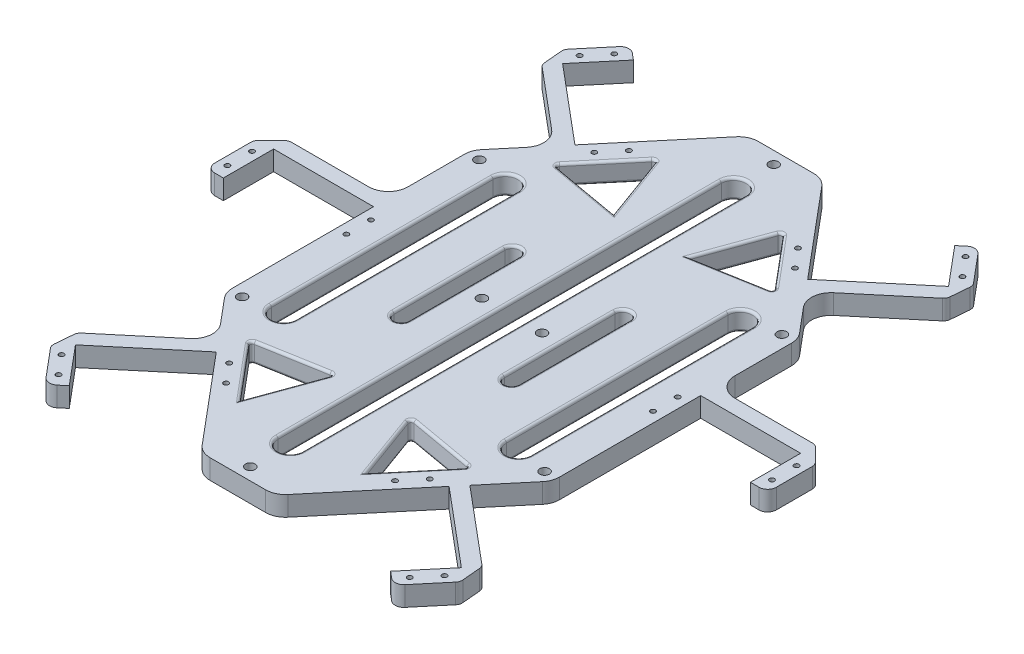
SolidWorks part; units mm, degrees
material "ABS"
ref_plane "Front Plane" through (0, 0, 0) normal (0, 0, 1) x (1, 0, 0)
ref_plane "Top Plane" through (0, 0, 0) normal (0, 1, 0) x (1, 0, 0)
ref_plane "Right Plane" through (0, 0, 0) normal (1, 0, 0) x (0, 0, -1)
sketch "Sketch1" plane through (0, 0, 0) normal (0, 1, 0) x (1, 0, 0)
  line L14 (0, 0) -> (0, 100)
  line L21 (0, 100) -> (51.423, 161.2836)
  line L22 (51.423, 161.2836) -> (81.423, 161.2836)
  line L23 (81.423, 161.2836) -> (132.846, 100)
  line L24 (132.846, 100) -> (132.846, 0)
  line L25 (132.846, 0) -> (81.423, -61.2836)
  line L26 (81.423, -61.2836) -> (51.423, -61.2836)
  line L27 (51.423, -61.2836) -> (0, 0)
  dimension "D4" = 80
  dimension "D1" = 100
  dimension "D2" = 80
  dimension "D3" = 30
  dimension "D5" = 80
  dimension "D6" = 30
  dimension "D7" = 140
  dimension "D8" = 140
  dimension "D9" = 140
  dimension "D10" = 140
extrude "Boss-Extrude1" add sketch "Sketch1" along normal blind 8
sketch "Sketch2" plane through (0, 8, 0) normal (0, 1, 0) x (1, 0, 0)
  line L0 (0, 50) -> (132.846, 50) construction
  line L1 (0, 100) -> (0, 0) construction
  line L2 (132.846, 0) -> (132.846, 100) construction
  line L3 (66.423, 161.2836) -> (66.423, -61.2836) construction
  line L4 (81.423, 161.2836) -> (51.423, 161.2836) construction
  line L5 (51.423, -61.2836) -> (81.423, -61.2836) construction
  line L6 (25.7115, -30.6418) -> (11.6576, -42.4344) construction
  line L7 (39.773, -0.8) -> (93.073, -0.8) construction
  line L8 (39.773, -0.8) -> (39.773, 100.8) construction
  line L9 (39.773, 100.8) -> (93.073, 100.8) construction
  line L10 (93.073, -0.8) -> (93.073, 100.8) construction
  line L11 (39.773, -0.8) -> (93.073, 100.8) construction
  line L12 (39.773, 100.8) -> (93.073, -0.8) construction
  line L13 (0, 0) -> (51.423, -61.2836) construction
  circle A5 centre (25.6767, -24.144) radius 1
  circle A6 centre (32.1045, -31.8044) radius 1
  circle A7 centre (4.15, 55) radius 1
  circle A8 centre (4.15, 45) radius 1
  circle A9 centre (32.1045, 131.8044) radius 1
  circle A10 centre (25.6767, 124.144) radius 1
  circle A11 centre (107.1694, 124.144) radius 1
  circle A12 centre (100.7415, 131.8044) radius 1
  circle A13 centre (128.696, 45) radius 1
  circle A14 centre (128.696, 55) radius 1
  circle A15 centre (100.7415, -31.8044) radius 1
  circle A16 centre (107.1694, -24.144) radius 1
  point P12 (66.423, 50)
  dimension "D15" = 2
  dimension "D16" = 2
  dimension "D21" = 2
  dimension "D22" = 2
  dimension "D1" = 101.6
  dimension "D2" = 53.3
  dimension "D17" = 4.15
  dimension "D18" = 4.15
  dimension "D19" = 10
  dimension "D20" = 5
  dimension "D23" = 4.15
  dimension "D24" = 4.15
  dimension "D25" = 10
  dimension "D26" = 5
extrude "mounting holes" cut sketch "Sketch2" against normal through all
sketch "Sketch3" plane through (0, 8, 0) normal (0, 1, 0) x (1, 0, 0)
  line L0 (66.423, 161.2836) -> (66.423, -61.2836) construction
  line L1 (81.423, 161.2836) -> (51.423, 161.2836) construction
  line L2 (51.423, -61.2836) -> (81.423, -61.2836) construction
  line L3 (0, 50) -> (132.846, 50) construction
  line L4 (0, 100) -> (0, 0) construction
  line L5 (132.846, 0) -> (132.846, 100) construction
  line L6 (66.423, 140) -> (66.423, -40) construction
  line L7 (71.423, 140) -> (71.423, -40)
  line L8 (61.423, 140) -> (61.423, -40)
  line L12 (18.7108, 5) -> (18.7108, 95) construction
  line L13 (13.7108, 5) -> (13.7108, 95)
  line L14 (23.7108, 5) -> (23.7108, 95)
  line L15 (21.5683, -11.7715) -> (40.8519, -34.7528)
  line L16 (40.8519, -34.7528) -> (51.1125, -6.562)
  line L17 (51.1125, -6.562) -> (21.5683, -11.7715)
  line L18 (0, 0) -> (51.423, -61.2836) construction
  line L22 (44.023, 72.5) -> (44.023, 27.5) construction
  line L23 (47.023, 72.5) -> (47.023, 27.5)
  line L24 (41.023, 72.5) -> (41.023, 27.5)
  line L25 (21.5683, 111.7715) -> (40.8519, 134.7528)
  line L26 (40.8519, 134.7528) -> (51.1125, 106.562)
  line L27 (51.1125, 106.562) -> (21.5683, 111.7715)
  line L28 (111.2777, -11.7715) -> (91.9941, -34.7528)
  line L29 (91.9941, -34.7528) -> (81.7335, -6.562)
  line L30 (81.7335, -6.562) -> (111.2777, -11.7715)
  line L31 (88.823, 72.5) -> (88.823, 27.5) construction
  line L32 (85.823, 72.5) -> (85.823, 27.5)
  line L33 (91.823, 72.5) -> (91.823, 27.5)
  line L34 (114.1353, 5) -> (114.1353, 95) construction
  line L35 (119.1353, 5) -> (119.1353, 95)
  line L36 (109.1353, 5) -> (109.1353, 95)
  line L37 (81.7335, 106.562) -> (111.2777, 111.7715)
  line L38 (91.9941, 134.7528) -> (81.7335, 106.562)
  line L39 (111.2777, 111.7715) -> (91.9941, 134.7528)
  arc A0 (71.423, 140) -> (61.423, 140) centre (66.423, 140) ccw
  arc A1 (61.423, -40) -> (71.423, -40) centre (66.423, -40) ccw
  arc A2 (13.7108, 5) -> (23.7108, 5) centre (18.7108, 5) ccw
  arc A3 (23.7108, 95) -> (13.7108, 95) centre (18.7108, 95) ccw
  arc A4 (47.023, 72.5) -> (41.023, 72.5) centre (44.023, 72.5) ccw
  arc A5 (41.023, 27.5) -> (47.023, 27.5) centre (44.023, 27.5) ccw
  arc A6 (85.823, 72.5) -> (91.823, 72.5) centre (88.823, 72.5) cw
  arc A7 (91.823, 27.5) -> (85.823, 27.5) centre (88.823, 27.5) cw
  arc A8 (119.1353, 5) -> (109.1353, 5) centre (114.1353, 5) cw
  arc A9 (109.1353, 95) -> (119.1353, 95) centre (114.1353, 95) cw
  point P14 (66.423, 50)
  point P23 (18.7108, 50)
  point P32 (44.023, 50)
  point P46 (88.823, 50)
  point P53 (114.1353, 50)
  dimension "D2" = 180
  dimension "D3" = 5
  dimension "D8" = 3
  dimension "D1" = 90
  dimension "D4" = 30
  dimension "D5" = 30
  dimension "D6" = 30
  dimension "D7" = 45
  dimension "D9" = 25.4
extrude "Cut-Extrude1" cut sketch "Sketch3" against normal through all
sketch "Sketch4" plane through (0, 8, 0) normal (0, 1, 0) x (1, 0, 0)
  line L0 (25.7115, -30.6418) -> (-23.1285, -71.6234) construction
  line L1 (0, 0) -> (51.423, -61.2836) construction
  line L2 (0, 50) -> (-64.2755, 50) construction
  line L3 (0, 100) -> (0, 0) construction
  line L4 (25.7115, 130.6418) -> (-14.5433, 164.4196) construction
  line L5 (51.423, 161.2836) -> (0, 100) construction
  line L6 (107.1345, 130.6418) -> (143.3112, 160.9976) construction
  line L7 (132.846, 100) -> (81.423, 161.2836) construction
  line L8 (132.846, 50) -> (189.4522, 50) construction
  line L9 (132.846, 0) -> (132.846, 100) construction
  line L10 (107.1345, -30.6418) -> (151.3622, -67.7532) construction
  line L11 (81.423, -61.2836) -> (132.846, 0) construction
  line L12 (-11.3581, -48.6928) -> (19.2836, -22.9813) construction
  line L13 (19.2836, -22.9813) -> (32.1394, -38.3022) construction
  line L14 (32.1394, -38.3022) -> (1.4976, -64.0137) construction
  line L15 (1.4976, -64.0137) -> (-11.3581, -48.6928) construction
  line L24 (-5.3899, -56.739) -> (-18.1892, -41.4853) construction
  line L25 (1.2652, -37.8395) -> (19.1551, -22.8281) construction
  line L26 (19.1551, -22.8281) -> (-11.9463, -48.9253)
  line L27 (-1.778, -67.0233) -> (8.4573, -58.435) construction
  line L28 (-11.9463, -48.9253) -> (1.1665, -64.5526)
  line L29 (1.1665, -64.5526) -> (-4.1958, -69.0521)
  line L30 (-4.1958, -69.0521) -> (-21.1654, -48.8285)
  line L31 (-21.1654, -48.8285) -> (15.2983, -18.2319)
  line L32 (15.2983, -18.2319) -> (19.1551, -22.8281)
  line L33 (0, 60.2) -> (-40.6, 60.2)
  line L34 (-40.6, 60.2) -> (-40.6, 39.8)
  line L35 (-40.6, 39.8) -> (-47.6, 39.8)
  line L36 (-47.6, 39.8) -> (-47.6, 66.2)
  line L37 (-47.6, 66.2) -> (0, 66.2)
  line L38 (0, 66.2) -> (0, 60.2)
  line L39 (1.1665, 164.5526) -> (-4.1958, 169.0521)
  line L40 (-4.1958, 169.0521) -> (-21.1654, 148.8285)
  line L41 (-11.9463, 148.9253) -> (1.1665, 164.5526)
  line L42 (-21.1654, 148.8285) -> (15.2983, 118.2319)
  line L43 (15.2983, 118.2319) -> (19.1551, 122.8281)
  line L44 (19.1551, 122.8281) -> (-11.9463, 148.9253)
  line L45 (66.423, -61.2836) -> (66.423, 161.2836) construction
  line L46 (51.423, -61.2836) -> (81.423, -61.2836) construction
  line L47 (81.423, 161.2836) -> (51.423, 161.2836) construction
  line L48 (134.624, -67.0233) -> (124.3888, -58.435) construction
  line L49 (131.5808, -37.8395) -> (113.6909, -22.8281) construction
  line L50 (138.2359, -56.739) -> (151.0352, -41.4853) construction
  line L51 (131.3484, -64.0137) -> (144.2042, -48.6928) construction
  line L52 (100.7066, -38.3022) -> (131.3484, -64.0137) construction
  line L53 (113.5624, -22.9813) -> (100.7066, -38.3022) construction
  line L54 (144.2042, -48.6928) -> (113.5624, -22.9813) construction
  line L55 (107.1345, 130.6418) -> (147.3894, 164.4196) construction
  line L56 (132.846, 50) -> (197.1216, 50) construction
  line L57 (107.1345, -30.6418) -> (155.9746, -71.6234) construction
  line L58 (113.6909, 122.8281) -> (144.7924, 148.9253)
  line L59 (117.5477, 118.2319) -> (113.6909, 122.8281)
  line L60 (154.0114, 148.8285) -> (117.5477, 118.2319)
  line L61 (144.7924, 148.9253) -> (131.6795, 164.5526)
  line L62 (137.0418, 169.0521) -> (154.0114, 148.8285)
  line L63 (131.6795, 164.5526) -> (137.0418, 169.0521)
  line L64 (132.846, 66.2) -> (132.846, 60.2)
  line L65 (180.446, 66.2) -> (132.846, 66.2)
  line L66 (180.446, 39.8) -> (180.446, 66.2)
  line L67 (173.446, 39.8) -> (180.446, 39.8)
  line L68 (173.446, 60.2) -> (173.446, 39.8)
  line L69 (132.846, 60.2) -> (173.446, 60.2)
  line L70 (117.5477, -18.2319) -> (113.6909, -22.8281)
  line L71 (154.0114, -48.8285) -> (117.5477, -18.2319)
  line L72 (137.0418, -69.0521) -> (154.0114, -48.8285)
  line L73 (131.6795, -64.5526) -> (137.0418, -69.0521)
  line L74 (144.7924, -48.9253) -> (131.6795, -64.5526)
  line L75 (113.6909, -22.8281) -> (144.7924, -48.9253)
  dimension "D1" = 40
  dimension "D2" = 20
  dimension "D3" = 40
  dimension "D4" = 40.6
  dimension "D5" = 0.2
  dimension "D6" = 0.2
  dimension "D7" = 7
  dimension "D8" = 26.4
  dimension "D9" = 10.2
  dimension "D10" = 40.6
  dimension "D11" = 20.4
  dimension "D12" = 7
  dimension "D13" = 26.4
  dimension "D14" = 10.2
extrude "Boss-Extrude2" add sketch "Sketch4" against normal blind 8
sketch "Sketch5" plane through (0, 8, 0) normal (0, 1, 0) x (1, 0, 0)
  line L0 (25.6767, -24.144) -> (32.1045, -31.8044) construction
  line L1 (28.8906, -27.9742) -> (21.384, -34.273) construction
  line L2 (4.15, 55) -> (4.15, 45) construction
  line L3 (4.15, 50) -> (-23.5507, 50) construction
  line L4 (71.423, 50) -> (32.1045, 50) construction
  line L5 (71.423, -40) -> (71.423, 140) construction
  line L6 (66.423, -61.2836) -> (66.423, 0) construction
  line L7 (51.423, -61.2836) -> (81.423, -61.2836) construction
  circle A0 centre (-11.3233, -55.1906) radius 1
  circle A1 centre (-4.8954, -62.8511) radius 1
  circle A2 centre (-44.15, 55) radius 1
  circle A3 centre (-44.15, 45) radius 1
  circle A4 centre (-4.8954, 162.8511) radius 1
  circle A5 centre (-11.3233, 155.1906) radius 1
  circle A6 centre (144.1693, 155.1906) radius 1
  circle A7 centre (137.7414, 162.8511) radius 1
  circle A8 centre (176.996, 45) radius 1
  circle A9 centre (176.996, 55) radius 1
  circle A10 centre (137.7414, -62.8511) radius 1
  circle A11 centre (144.1693, -55.1906) radius 1
  dimension "D1" = 2
  dimension "D2" = 2
  dimension "D7" = 2
  dimension "D8" = 2
  dimension "D3" = 48.3
  dimension "D4" = 48.3
  dimension "D5" = 10
  dimension "D6" = 5
  dimension "D9" = 10
  dimension "D10" = 5
  dimension "D11" = 48.3
  dimension "D12" = 48.3
extrude "Cut-Extrude2" cut sketch "Sketch5" against normal through all
fillet "Fillet1" radius 8 1 edges at (15.2983, 4, -118.2319)
fillet "Fillet2" radius 8 1 edges at (0, 4, -100)
fillet "Fillet3" radius 8 1 edges at (51.423, 4, -161.2836)
fillet "Fillet4" radius 8 1 edges at (0, 4, 0)
fillet "Fillet5" radius 8 1 edges at (132.846, 4, -100)
fillet "Fillet6" radius 8 1 edges at (81.423, 4, 61.2836)
fillet "Fillet7" radius 8 1 edges at (81.423, 4, -161.2836)
fillet "Fillet8" radius 8 1 edges at (51.423, 4, 61.2836)
fillet "Fillet9" radius 8 1 edges at (132.846, 4, 0)
fillet "Fillet10" radius 8 1 edges at (132.846, 4, -66.2)
fillet "Fillet11" radius 8 1 edges at (117.5477, 4, -118.2319)
fillet "Fillet12" radius 8 1 edges at (15.2983, 4, 18.2319)
fillet "Fillet13" radius 8 1 edges at (0, 4, -66.2)
fillet "Fillet16" radius 1 72 edges at (96.5056, 0, -109.1667) (96.5056, 8, -109.1667) (86.8638, 0, -120.6574) (86.8638, 8, -120.6574) (45.9822, 0, -120.6574) (45.9822, 8, -120.6574) (36.3404, 0, -109.1667) (36.3404, 8, -109.1667) (45.9822, 0, 20.6574) (45.9822, 8, 20.6574) (31.2101, 0, 23.2621) (31.2101, 8, 23.2621) (101.6359, 0, 23.2621) (101.6359, 8, 23.2621) (86.8638, 0, 20.6574) (86.8638, 8, 20.6574) (114.1353, 0, -100) (119.1353, 0, -50) (114.1353, 0, 0) (114.1353, 8, -100) (119.1353, 8, -50) (114.1353, 8, 0) (18.7108, 0, -100) (23.7108, 0, -50) (18.7108, 0, 0) (18.7108, 8, -100) (23.7108, 8, -50) (18.7108, 8, 0) (88.823, 0, -75.5) (91.823, 0, -50) (88.823, 0, -24.5) (88.823, 8, -75.5) (91.823, 8, -50) (88.823, 8, -24.5) (44.023, 0, -75.5) (47.023, 0, -50) (44.023, 0, -24.5) (44.023, 8, -75.5) (47.023, 8, -50) (44.023, 8, -24.5) (66.423, 8, -145) (71.423, 8, -50) (66.423, 8, 45) (111.2777, 4, -111.7715) (101.6359, 0, -123.2621) (91.9941, 4, -134.7528) (101.6359, 8, -123.2621) (40.8519, 4, -134.7528) (31.2101, 0, -123.2621) (21.5683, 4, -111.7715) (31.2101, 8, -123.2621) (51.1125, 4, 6.562) (36.3404, 0, 9.1667) (21.5683, 4, 11.7715) (36.3404, 8, 9.1667) (111.2777, 4, 11.7715) (96.5056, 0, 9.1667) (81.7335, 4, 6.562) (96.5056, 8, 9.1667) (109.1353, 0, -50) (109.1353, 8, -50) (13.7108, 0, -50) (13.7108, 8, -50) (85.823, 0, -50) (85.823, 8, -50) (41.023, 0, -50) (41.023, 8, -50) (61.423, 8, -50) (66.423, 0, 45) (61.423, 0, -50) (66.423, 0, -145) (71.423, 0, -50)
fillet "Fillet18" radius 3.5 6 edges at (-47.6, 4, -39.8) (137.0418, 4, 69.0521) (180.446, 4, -39.8) (137.0418, 4, -169.0521) (-4.1958, 4, -169.0521) (-4.1958, 4, 69.0521)
chamfer "Chamfer2" distance 7 angle 45 6 edges at (-21.1654, 4, 48.8285) (154.0114, 4, 48.8285) (180.446, 4, -66.2) (154.0114, 4, -148.8285) (-21.1654, 4, -148.8285) (-47.6, 4, -66.2)
fillet "Fillet21" radius 3 12 edges at (-15.8031, 4, 44.329) (-16.6659, 4, 54.1909) (-16.6659, 4, -154.1909) (-15.8031, 4, -144.329) (-47.6, 4, -59.2) (-40.6, 4, -66.2) (148.6491, 4, -144.329) (149.5119, 4, -154.1909) (180.446, 4, -59.2) (173.446, 4, -66.2) (148.6491, 4, 44.329) (149.5119, 4, 54.1909)
sketch "Sketch6" plane through (0, 8, 0) normal (0, 1, 0) x (1, 0, 0)
  line L0 (55.1535, -61.2836) -> (77.6925, -61.2836) construction
  line L1 (72.423, 50) -> (84.823, 50) construction
  line L2 (0, 60.2) -> (0, 2.9118) construction
  line L3 (1.8716, -2.2305) -> (10.156, -12.1035) construction
  line L4 (61.423, 50) -> (-15.6642, 50) construction
  line L5 (61.423, 140) -> (61.423, -40) construction
  line L6 (66.423, -46) -> (66.423, 68.6161) construction
  line L7 (66.423, -61.2836) -> (66.423, -50.8457) construction
  line L8 (72.423, 140) -> (72.423, -40) construction
  line L9 (84.823, 27.5) -> (84.823, 72.5) construction
  line L10 (48.023, 56.8269) -> (60.423, 56.8269) construction
  line L11 (48.023, 72.5) -> (48.023, 27.5) construction
  line L12 (60.423, -40) -> (60.423, 140) construction
  circle A0 centre (66.423, -56.2836) radius 1.95
  circle A1 centre (5, 1.8199) radius 1.95
  arc A2 (60.423, -40) -> (72.423, -40) centre (66.423, -40) ccw construction
  circle A3 centre (66.423, 156.2836) radius 1.95
  circle A4 centre (5, 98.1801) radius 1.95
  circle A5 centre (127.846, 98.1801) radius 1.95
  circle A7 centre (127.846, 1.8199) radius 1.95
  circle A8 centre (78.623, 50) radius 1.95
  circle A9 centre (54.223, 50) radius 1.95
  point P46 (0, 0)
  point P47 (54.223, 56.8269)
  dimension "D1" = 3.9
  dimension "D4" = 3.9
  dimension "D3" = 3.9
  dimension "D7" = 3.9
  dimension "D2" = 5
  dimension "D5" = 5
  dimension "D6" = 5
extrude "Cut-Extrude3" cut sketch "Sketch6" against normal through all
sketch "Sketch7" plane through (0, 0, 0) normal (0, -1, 0) x (1, 0, 0)
  line L0 (66.423, 61.2836) -> (66.423, -17.1865) construction
  line L1 (55.1535, 61.2836) -> (77.6925, 61.2836) construction
  line L3 (66.423, 15.2836) -> (41.5404, 15.2836) construction
  line L5 (66.423, -161.2836) -> (66.423, 61.2836) construction
  line L6 (77.6925, -161.2836) -> (55.1535, -161.2836) construction
  line L7 (66.423, -50) -> (153.1245, -50) construction
  circle A4 centre (54.173, 48.6836) radius 1.5
  circle A6 centre (78.673, 48.6836) radius 1.5
  circle A7 centre (78.673, -18.1164) radius 1.5
  circle A8 centre (54.173, -18.1164) radius 1.5
  dimension "D4" = 46
  dimension "D1" = 3
  dimension "D2" = 33.4
  dimension "D3" = 12.25
extrude "Cut-Extrude4" cut sketch "Sketch7" against normal blind 4
